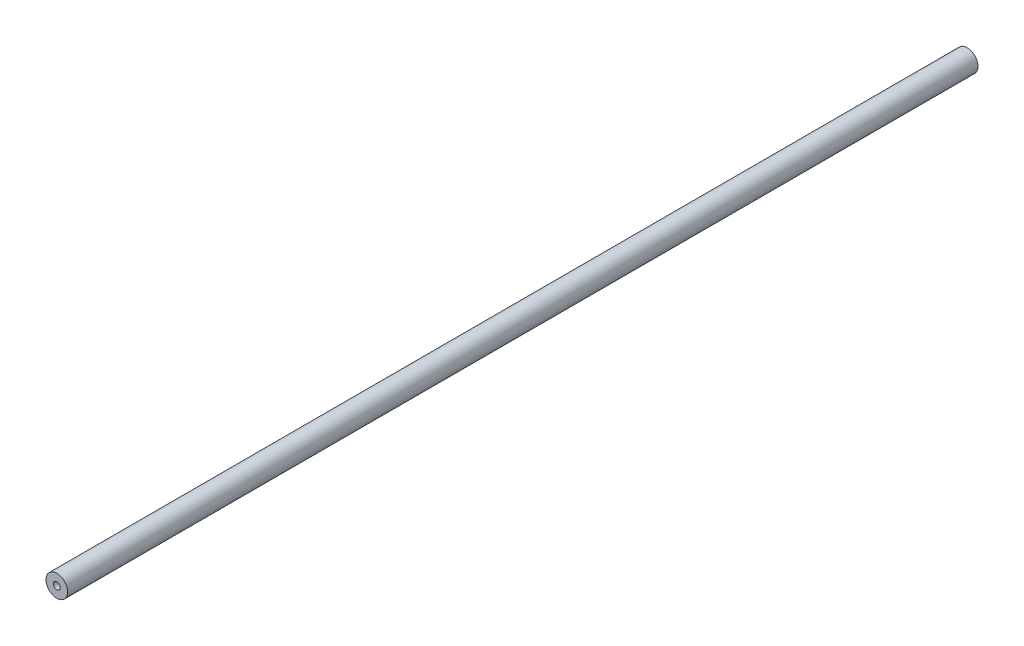
SolidWorks part; units mm, degrees
material "6061-T6 (SS)"
ref_plane "Front Plane" through (0, 0, 0) normal (0, 0, 1) x (1, 0, 0)
ref_plane "Top Plane" through (0, 0, 0) normal (0, 1, 0) x (1, 0, 0)
ref_plane "Right Plane" through (0, 0, 0) normal (1, 0, 0) x (0, 0, -1)
sketch "Sketch1" plane through (0, 0, 0) normal (0, 0, 1) x (1, 0, 0)
  circle A0 centre (0, 0) radius 6.35
  dimension "D1" = 12.7
extrude "Boss-Extrude1" add sketch "Sketch1" along normal blind 533.4
hole_wizard "#10-32 Tapped Hole1" positions "Sketch3" profile "Sketch2" tap size "#10-32" standard "ANSI Inch"
sketch "Sketch3" plane through (0, 0, 533.4) normal (0, 0, 1) x (1, 0, 0)
  point P0 (0, 0)
  point P1 (0, 0)
sketch "Sketch2" plane through (0, 0, 533.4) normal (1, 0, 0) x (0, -1, 0)
  line L0 (0, 0) -> (0, 14.9293)
  line L1 (0, 14.9293) -> (2.0193, 13.716)
  line L2 (2.0193, 13.716) -> (2.0193, 0)
  line L5 (2.0193, 0) -> (0, 0)
  line L10 (0, 14.9293) -> (-2.0193, 13.716) construction
  line L11 (0, -6.35) -> (0, 107.95) construction
  dimension "Tap Drill Dia." = 4.0386
  dimension "Tap Drill Depth" = 13.716
  dimension "Drill Angle" = 118
cosmetic thread "Hole Thread1"
hole_wizard "#10-32 Tapped Hole2" positions "Sketch5" profile "Sketch4" tap size "#10-32" standard "ANSI Inch"
sketch "Sketch5" plane through (0, 0, 0) normal (0, 0, -1) x (-1, 0, 0)
  point P0 (0, 0)
  point P1 (0, 0)
sketch "Sketch4" plane through (0, 0, 0) normal (1, 0, 0) x (0, 1, 0)
  line L0 (0, 0) -> (0, 14.9293)
  line L1 (0, 14.9293) -> (2.0193, 13.716)
  line L2 (2.0193, 13.716) -> (2.0193, 0)
  line L5 (2.0193, 0) -> (0, 0)
  line L10 (0, 14.9293) -> (-2.0193, 13.716) construction
  line L11 (0, -6.35) -> (0, 107.95) construction
  dimension "Tap Drill Dia." = 4.0386
  dimension "Tap Drill Depth" = 13.716
  dimension "Drill Angle" = 118
cosmetic thread "Hole Thread2"
